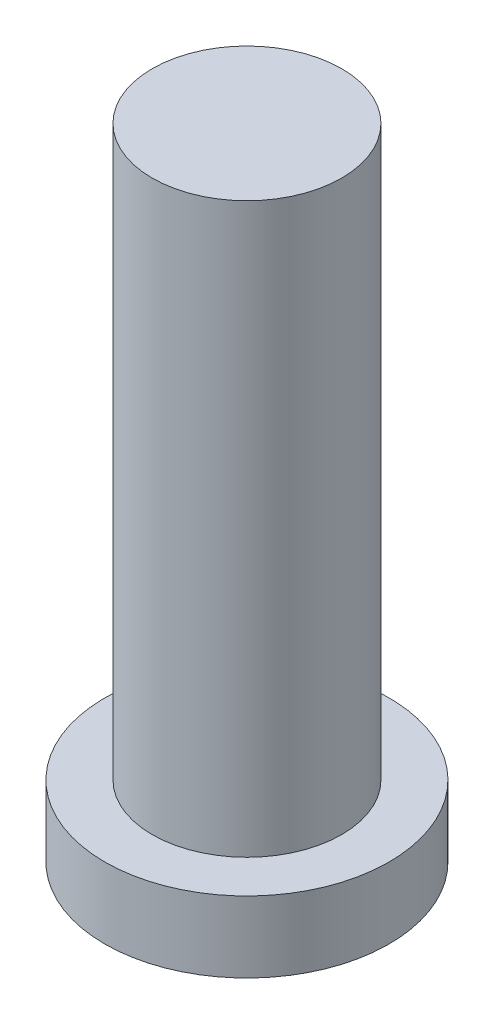
SolidWorks part; units mm, degrees
ref_plane "Front Plane" through (0, 0, 0) normal (0, 0, 1) x (1, 0, 0)
ref_plane "Top Plane" through (0, 0, 0) normal (0, 1, 0) x (1, 0, 0)
ref_plane "Right Plane" through (0, 0, 0) normal (1, 0, 0) x (0, 0, -1)
sketch "Sketch2" plane through (0, 0, 0) normal (0, 1, 0) x (1, 0, 0)
  circle A0 centre (0, 0) radius 3
extrude "Boss-Extrude1" add sketch "Sketch2" along normal blind 1.5
sketch "Sketch3" plane through (0, 1.5, 0) normal (0, 1, 0) x (1, 0, 0)
  circle A0 centre (0, 0) radius 2
extrude "Boss-Extrude2" add sketch "Sketch3" along normal blind 12
